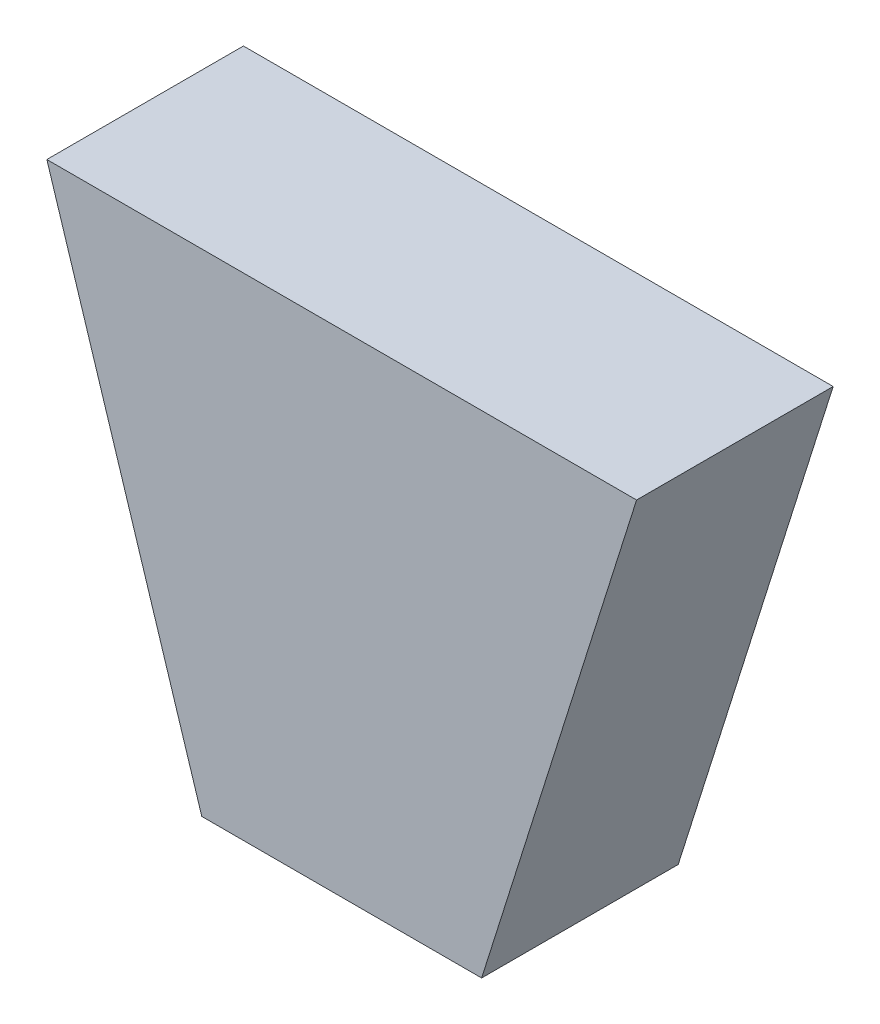
SolidWorks part; units mm, degrees
ref_plane "Спереди" through (0, 0, 0) normal (0, 0, 1) x (1, 0, 0)
ref_plane "Сверху" through (0, 0, 0) normal (0, 1, 0) x (1, 0, 0)
ref_plane "Справа" through (0, 0, 0) normal (1, 0, 0) x (0, 0, -1)
sketch "Эскиз1" plane through (0, 0, 0) normal (0, 0, 1) x (1, 0, 0)
  line L0 (0, 0) -> (-15.7649, 50)
  line L6 (44.2351, 50) -> (-15.7649, 50)
  line L7 (0, 0) -> (28.4701, 0)
  line L8 (28.4701, 0) -> (44.2351, 50)
  dimension "D1" = 50
  dimension "D2" = 72.5
  dimension "D3" = 72.5
  dimension "D4" = 60
  dimension "D5" = 28.4701
  dimension "D6" = 35
extrude "Бобышка-Вытянуть1" add sketch "Эскиз1" along normal blind 20
